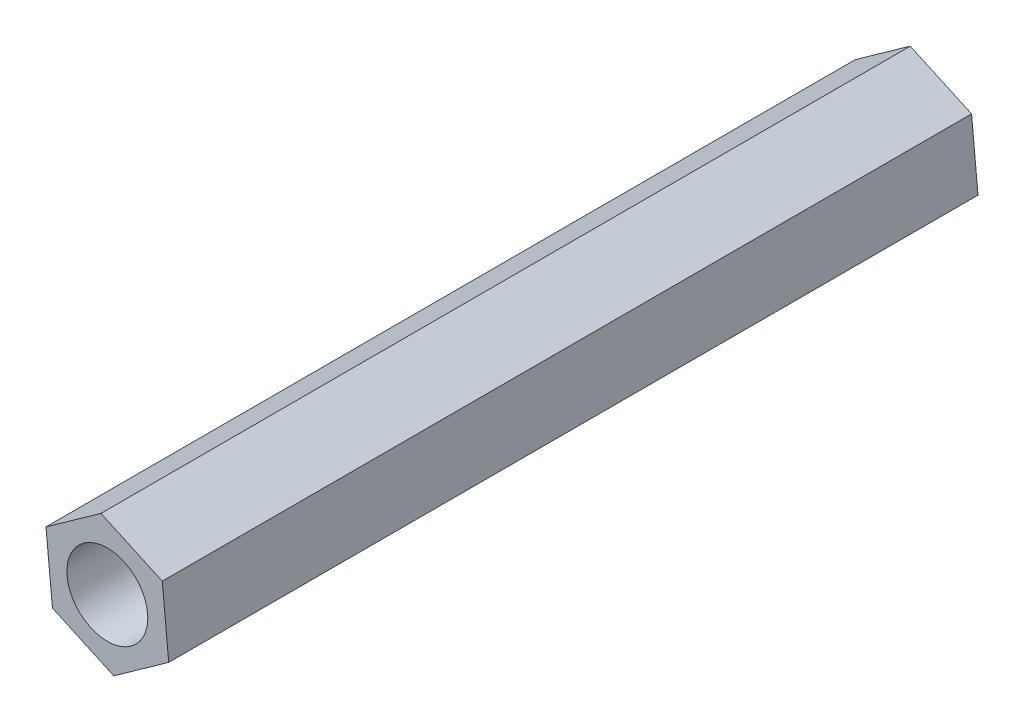
SolidWorks part; units mm, degrees
ref_plane "Front Plane" through (0, 0, 0) normal (0, 0, 1) x (1, 0, 0)
ref_plane "Top Plane" through (0, 0, 0) normal (0, 1, 0) x (1, 0, 0)
ref_plane "Right Plane" through (0, 0, 0) normal (1, 0, 0) x (0, 0, -1)
sketch "Sketch1" plane through (0, 0, 0) normal (0, 0, 1) x (1, 0, 0)
  line L1 (2.0364, 1.4502) -> (-0.2377, 2.4887)
  line L2 (-0.2377, 2.4887) -> (-2.2741, 1.0385)
  line L3 (-2.2741, 1.0385) -> (-2.0364, -1.4502)
  line L4 (-2.0364, -1.4502) -> (0.2377, -2.4887)
  line L5 (0.2377, -2.4887) -> (2.2741, -1.0385)
  line L6 (2.2741, -1.0385) -> (2.0364, 1.4502)
  circle A0 centre (0, 0) radius 1.5
  circle A1 centre (0, 0) radius 2.1651 construction
  dimension "D1" = 3
  dimension "D2" = 2.5
extrude "Boss-Extrude1" add sketch "Sketch1" along normal blind 30
